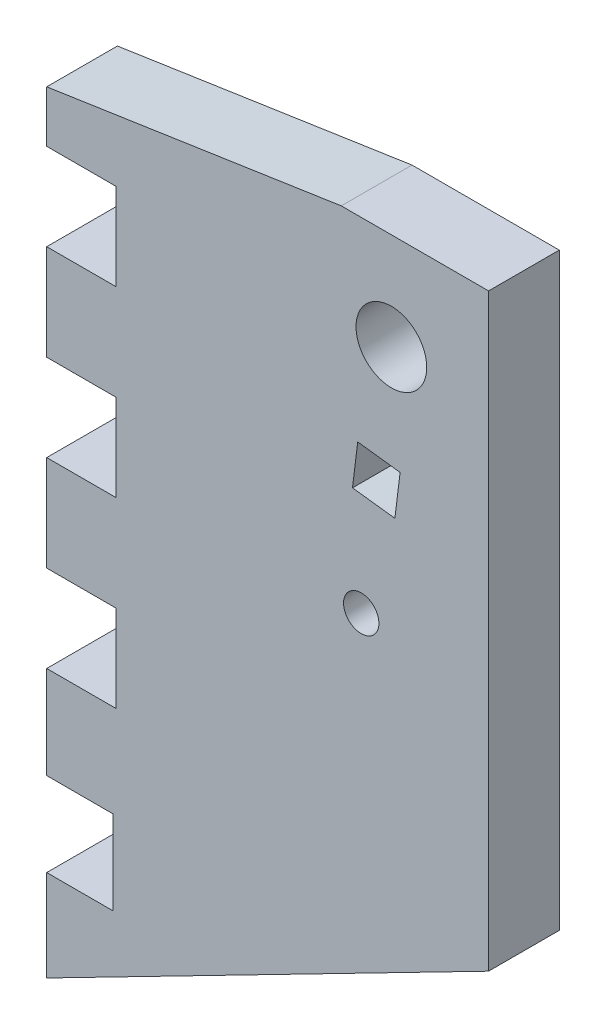
SolidWorks part; units mm, degrees
material "Thornel VCB-20 Carbon Cloth"
ref_plane "Front Plane" through (0, 0, 0) normal (0, 0, 1) x (1, 0, 0)
ref_plane "Top Plane" through (0, 0, 0) normal (0, 1, 0) x (1, 0, 0)
ref_plane "Right Plane" through (0, 0, 0) normal (1, 0, 0) x (0, 0, -1)
sketch "Sketch1" plane through (0, 0, 0) normal (0, 0, 1) x (1, 0, 0)
  line L0 (0, 0) -> (-38.1, 0)
  line L1 (0, 0) -> (0, -50.8)
  line L2 (-38.1, 0) -> (-38.1, -8.255)
  line L3 (-38.1, -8.255) -> (-32.131, -8.255)
  line L4 (-32.131, -8.255) -> (-32.131, -15.748)
  line L5 (-32.131, -15.748) -> (-38.1, -15.748)
  line L6 (-38.1, -47.244) -> (-38.1, -70.358)
  line L7 (-38.1, -15.748) -> (-38.1, -24.003)
  line L8 (-38.1, -24.003) -> (-32.131, -24.003)
  line L9 (-32.131, -24.003) -> (-32.131, -31.496)
  line L10 (-32.131, -31.496) -> (-38.1, -31.496)
  line L11 (-38.1, -31.496) -> (-38.1, -39.751)
  line L12 (-38.1, -39.751) -> (-32.131, -39.751)
  line L13 (-32.131, -39.751) -> (-32.131, -47.244)
  line L14 (-32.131, -47.244) -> (-38.1, -47.244)
  line L15 (-38.1, -70.358) -> (0, -50.8)
  circle A0 centre (-8.382, -8.382) radius 3.048
  dimension "D9" = 6.096
  dimension "D1" = 38.1
  dimension "D2" = 50.8
  dimension "D3" = 8.255
  dimension "D4" = 7.493
  dimension "D6" = 5.969
  dimension "D8" = 70.358
  dimension "D12" = 8.382
  dimension "D13" = 8.382
  dimension "D7" = 3
extrude "Boss-Extrude1" add sketch "Sketch1" along normal blind 6.096
sketch "Sketch2" plane through (0, 0, 0) normal (0, 0, -1) x (-1, 0, 0)
  line L5 (38.1, 0) -> (12.7, 0)
  line L6 (0, 0) -> (38.1, 0) construction
  line L7 (12.7, 0) -> (38.1, -3.81)
  line L8 (38.1, 0) -> (38.1, -8.255) construction
  line L9 (38.1, -3.81) -> (38.1, 0)
  dimension "D1" = 25.4
  dimension "D2" = 3.81
extrude "Cut-Extrude1" cut sketch "Sketch2" against normal blind 8.636
sketch "Sketch4" plane through (0, 0, 6.096) normal (0, 0, 1) x (1, 0, 0)
  line L0 (-38.1, -47.244) -> (-38.1, -55.245)
  line L1 (-38.1, -47.244) -> (-38.1, -70.358) construction
  line L2 (-38.1, -55.245) -> (-32.385, -55.245)
  line L3 (-32.385, -55.245) -> (-32.385, -62.484)
  line L4 (-32.385, -62.484) -> (-38.1, -62.484)
  line L5 (-38.1, -62.484) -> (-38.1, -55.245)
  line M18 (-38.1, -47.244) -> (-38.1, -70.358)
  dimension "D1" = 7.239
  dimension "D2" = 5.715
  dimension "D3" = 5.715
  dimension "D4" = 8.001
extrude "Cut-Extrude2" cut sketch "Sketch4" against normal through all contours L4 L3 L2 M18
sketch "Sketch5" plane through (0, 0, 0) normal (0, 0, -1) x (-1, 0, 0)
  line L0 (8.382, -8.382) -> (10.9822, -29.559) construction
  line L1 (8.382, -8.382) -> (8.382, -39.2411) construction
  line L2 (7.6299, -17.3671) -> (11.2855, -16.9183)
  line L3 (7.6299, -17.3671) -> (8.0788, -21.0227)
  line L4 (8.0788, -21.0227) -> (11.7343, -20.5738)
  line L5 (11.2855, -16.9183) -> (11.7343, -20.5738)
  circle A0 centre (8.382, -8.382) radius 3.048 construction
  circle A1 centre (10.9822, -29.559) radius 1.524
  dimension "D3" = 8.8265
  dimension "D7" = 3.048
  dimension "D1" = 21.336
  dimension "D2" = 7
  dimension "D4" = 1.8415
  dimension "D5" = 8.8265
  dimension "0.14" = 3.683
  dimension "D6" = 3.683
extrude "Cut-Extrude4" cut sketch "Sketch5" against normal up to surface (6.096 mm away) up to face at (-5.334, -8.382, 6.096)
ref_plane "Plane1" through (0, 0, 0) normal (0, 0, -1) x (-1, 0, 0)
